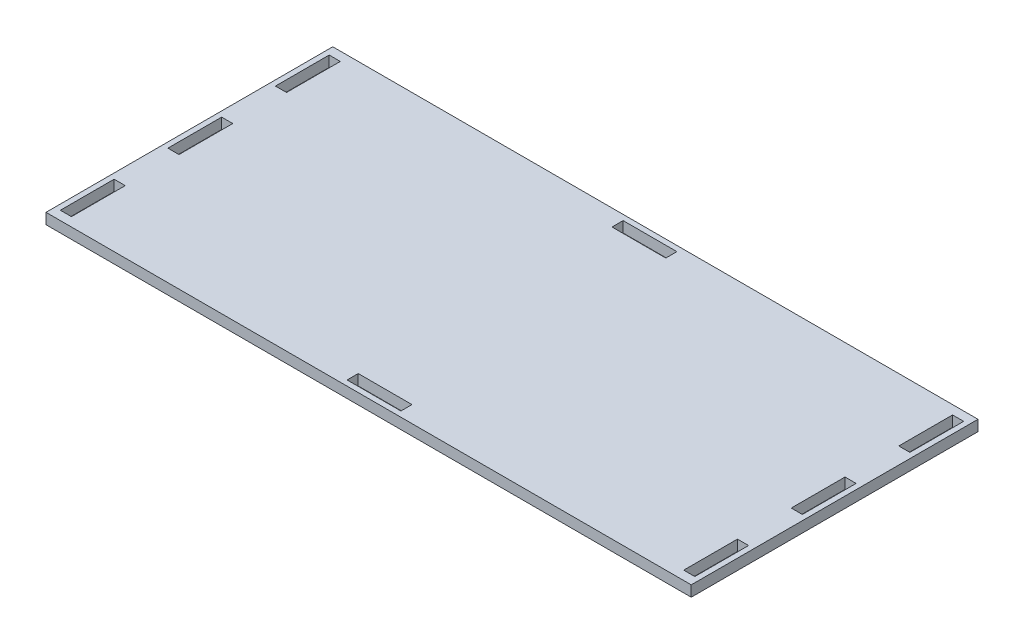
SolidWorks part; units mm, degrees
ref_plane "前视基准面" through (0, 0, 0) normal (0, 0, 1) x (1, 0, 0)
ref_plane "上视基准面" through (0, 0, 0) normal (0, 1, 0) x (1, 0, 0)
ref_plane "右视基准面" through (0, 0, 0) normal (1, 0, 0) x (0, 0, -1)
other "Configuration Table"
sketch "草图1" plane through (0, 0, 0) normal (0, 1, 0) x (1, 0, 0)
  line L0 (0, 61.0991) -> (0, -64.6496) construction
  line L1 (-90, -40) -> (90, -40)
  line L2 (-90, -40) -> (-90, 40)
  line L3 (-90, 40) -> (90, 40)
  line L4 (90, -40) -> (90, 40)
  line L5 (-90, -40) -> (90, 40) construction
  line L6 (-90, 40) -> (90, -40) construction
  line L7 (-88.5, 37.5) -> (-85.4, 37.5)
  line L8 (-88.5, 37.5) -> (-88.5, 22.5)
  line L9 (-88.5, 22.5) -> (-85.4, 22.5)
  line L10 (-85.4, 37.5) -> (-85.4, 22.5)
  line L11 (-88.5, 7.5) -> (-85.4, 7.5)
  line L12 (-88.5, 7.5) -> (-88.5, -7.5)
  line L13 (-88.5, -7.5) -> (-85.4, -7.5)
  line L14 (-85.4, 7.5) -> (-85.4, -7.5)
  line L15 (-88.5, -22.5) -> (-85.4, -22.5)
  line L16 (-88.5, -22.5) -> (-88.5, -37.5)
  line L17 (-88.5, -37.5) -> (-85.4, -37.5)
  line L18 (-85.4, -22.5) -> (-85.4, -37.5)
  line L19 (88.5, -37.5) -> (85.4, -37.5)
  line L20 (85.4, -22.5) -> (85.4, -37.5)
  line L21 (88.5, -22.5) -> (88.5, -37.5)
  line L22 (88.5, -22.5) -> (85.4, -22.5)
  line L23 (85.4, 7.5) -> (85.4, -7.5)
  line L24 (88.5, -7.5) -> (85.4, -7.5)
  line L25 (88.5, 7.5) -> (88.5, -7.5)
  line L26 (88.5, 7.5) -> (85.4, 7.5)
  line L27 (88.5, 22.5) -> (85.4, 22.5)
  line L28 (85.4, 37.5) -> (85.4, 22.5)
  line L29 (88.5, 37.5) -> (85.4, 37.5)
  line L30 (88.5, 37.5) -> (88.5, 22.5)
  line L31 (88.5, -37.5) -> (85.4, -37.5)
  line L32 (88.5, -22.5) -> (88.5, -37.5)
  line L33 (85.4, -22.5) -> (85.4, -37.5)
  line L34 (88.5, -22.5) -> (85.4, -22.5)
  line L35 (88.5, -7.5) -> (85.4, -7.5)
  line L36 (88.5, 7.5) -> (88.5, -7.5)
  line L37 (85.4, 7.5) -> (85.4, -7.5)
  line L38 (88.5, 7.5) -> (85.4, 7.5)
  line L39 (88.5, 22.5) -> (85.4, 22.5)
  line L40 (88.5, 37.5) -> (88.5, 22.5)
  line L41 (88.5, 37.5) -> (85.4, 37.5)
  line L42 (85.4, 37.5) -> (85.4, 22.5)
  line L43 (-93.4104, 0) -> (94.8742, 0) construction
  line L44 (-7.5, -35.4) -> (7.5, -35.4)
  line L45 (-7.5, -35.4) -> (-7.5, -38.5)
  line L46 (-7.5, -38.5) -> (7.5, -38.5)
  line L47 (7.5, -35.4) -> (7.5, -38.5)
  line L48 (-7.5, 38.5) -> (7.5, 38.5)
  line L49 (-7.5, 35.4) -> (-7.5, 38.5)
  line L50 (7.5, 35.4) -> (7.5, 38.5)
  line L51 (-7.5, 35.4) -> (7.5, 35.4)
  point P0 (0, 0)
  point P18 (-86.95, 7.5)
  dimension "D1" = 180
  dimension "D2" = 80
  dimension "D3" = 3.1
  dimension "D4" = 15
  dimension "D5" = 15
  dimension "D6" = 15
  dimension "D7" = 1.5
  dimension "D8" = 2.5
  dimension "D9" = 3.1
  dimension "D10" = 1.5
  dimension "D11" = 15
extrude "凸台-拉伸1" add sketch "草图1" along normal blind 3 contours L1 L4 L3 L2 L51 L49 L48 L50 L26 L25 L24 L23 L22 L21 L19 L20 L7 L10 L9 L8 L11 L14 L13 L12 L15 L18 L17 L16 L29 L30 L27 L28 L44 L47 L46 L45
